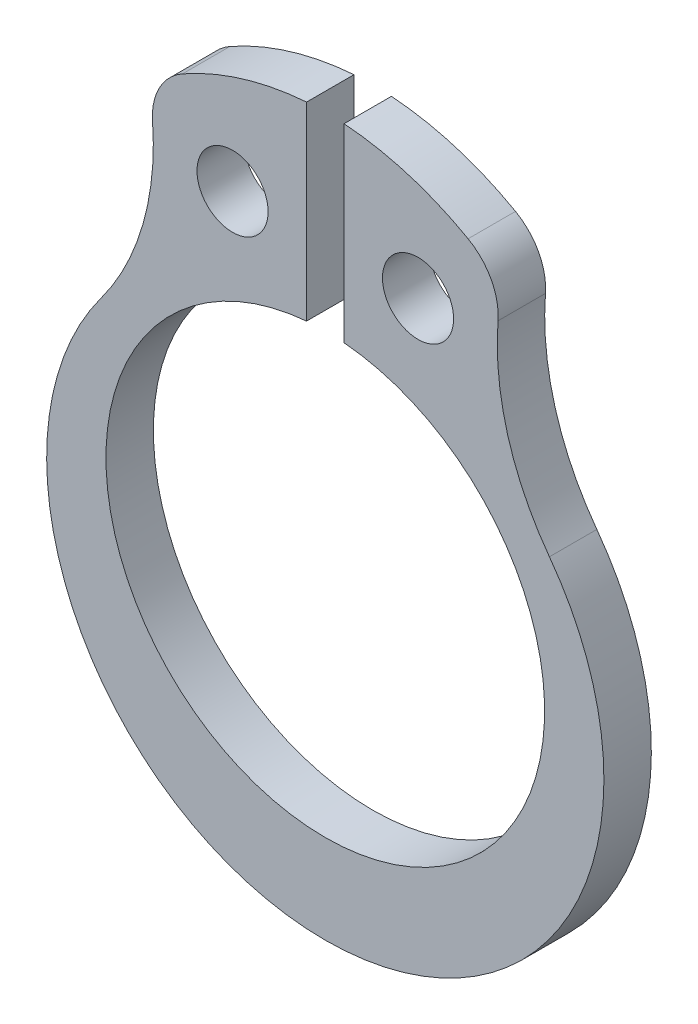
SolidWorks part; units mm, degrees
material "Plain Carbon Steel"
ref_plane "Front Plane" through (0, 0, 0) normal (0, 0, 1) x (1, 0, 0)
ref_plane "Top Plane" through (0, 0, 0) normal (0, 1, 0) x (1, 0, 0)
ref_plane "Right Plane" through (0, 0, 0) normal (1, 0, 0) x (0, 0, -1)
sketch "Sketch1" plane through (0, 0, 0) normal (0, 0, 1) x (1, 0, 0)
  line L0 (0, -1000) -> (0, 49000) construction
  line L1 (-1000, 0) -> (49000, 0) construction
  line L2 (-0.316, 6.8865) -> (-0.316, 3.6865)
  line L3 (0, 6.8865) -> (-0.316, 6.8865) construction
  line L4 (0.316, 6.8865) -> (0.316, 3.6865)
  circle A0 centre (0, 0) radius 3.7 construction
  circle A1 centre (0, 0) radius 5.2 construction
  arc A2 (-0.316, 6.8865) -> (-2.409, 6.252) centre (0.0529, 1.9001) ccw
  arc A3 (-2.409, 6.252) -> (-2.9137, 5.3059) centre (-1.9166, 5.3817) ccw
  arc A4 (-2.9137, 5.3059) -> (-3.7808, 2.292) centre (-7.4008, 4.9652) cw
  circle A5 centre (0, -0.5) radius 4.7 construction
  arc A6 (-3.7808, 2.292) -> (3.7808, 2.292) centre (0, -0.5) ccw
  arc A7 (-0.316, 3.6865) -> (0.316, 3.6865) centre (0, 0) ccw
  circle A8 centre (-1.5647, 4.959) radius 0.6
  arc A9 (2.9137, 5.3059) -> (3.7808, 2.292) centre (7.4008, 4.9652) ccw
  arc A10 (2.409, 6.252) -> (2.9137, 5.3059) centre (1.9166, 5.3817) cw
  arc A11 (0.316, 6.8865) -> (2.409, 6.252) centre (-0.0529, 1.9001) cw
  circle A12 centre (1.5647, 4.959) radius 0.6
  point P5 (0, -3.7)
  point P6 (0, -5.2)
  point P19 (0, 6.8865)
  dimension "D1" = 7.4
  dimension "D2" = 0.5
  dimension "D3" = 1.5
  dimension "D5" = 4.5
  dimension "D6" = 1
  dimension "D7" = 5
  dimension "D8" = 1.2
  dimension "D4" = 3.2
extrude "Boss-Extrude1" add sketch "Sketch1" along normal mid plane 0.8
